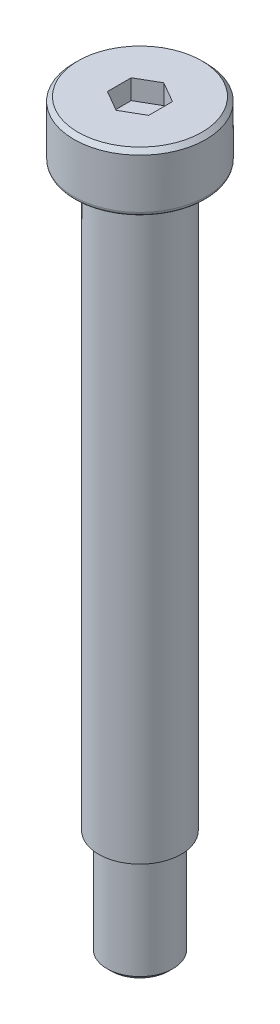
SolidWorks part; units mm, degrees
material "Plain Carbon Steel"
ref_plane "Front Plane" through (0, 0, 0) normal (0, 0, 1) x (1, 0, 0)
ref_plane "Top Plane" through (0, 0, 0) normal (0, 1, 0) x (1, 0, 0)
ref_plane "Right Plane" through (0, 0, 0) normal (1, 0, 0) x (0, 0, -1)
sketch "Sketch1" plane through (0, 0, 0) normal (0, 0, 1) x (1, 0, 0)
  line L0 (0, 0) -> (8, 0)
  line L1 (8, 0) -> (8, -7)
  line L2 (8, -7) -> (4.75, -7)
  line L3 (4.75, -7) -> (4.75, -7.5)
  line L4 (4.75, -7.5) -> (5, -7.5)
  line L5 (5, -7.5) -> (5, -77)
  line L6 (5, -77) -> (4, -77)
  line L7 (4, -77) -> (4, -90)
  line L8 (4, -90) -> (0, -90)
  line L9 (0, -90) -> (0, 0)
  line L10 (0, 5) -> (0, -95) construction
  dimension "D1" = 5
  dimension "D2" = 5
  dimension "D3" = 8
  dimension "D4" = 10
  dimension "D5" = 0.25
  dimension "D6" = 16
  dimension "Length" = 70
  dimension "D8" = 7
  dimension "D9" = 0.5
  dimension "D10" = 13
revolve "Revolve1" add sketch "Sketch1" angle 360 about L10
sketch "Sketch2" plane through (0, 0, 0) normal (0, 1, 0) x (1, 0, 0)
  line L1 (0, -2.8868) -> (2.5, -1.4434)
  line L2 (2.5, -1.4434) -> (2.5, 1.4434)
  line L3 (2.5, 1.4434) -> (0, 2.8868)
  line L4 (0, 2.8868) -> (-2.5, 1.4434)
  line L5 (-2.5, 1.4434) -> (-2.5, -1.4434)
  line L6 (-2.5, -1.4434) -> (0, -2.8868)
  circle A0 centre (0, 0) radius 2.5 construction
  dimension "D1" = 5
extrude "Cut-Extrude1" cut sketch "Sketch2" against normal blind 2.4
chamfer "Chamfer1" distance 0.5 angle 45 1 edges at (-8, 0, 0)
fillet "Fillet1" radius 0.5 1 edges at (-8, -7, 0)
chamfer "Chamfer2" distance 0.5 angle 45 1 edges at (-4, -90, 0)
